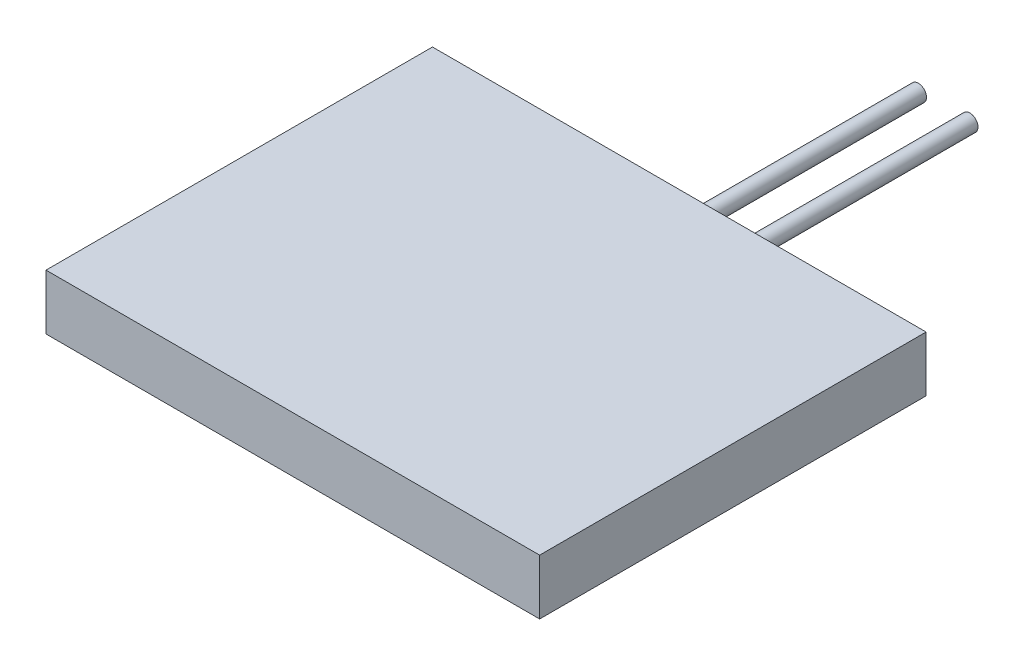
SolidWorks part; units mm, degrees
ref_plane "Front Plane" through (0, 0, 0) normal (0, 0, 1) x (1, 0, 0)
ref_plane "Top Plane" through (0, 0, 0) normal (0, 1, 0) x (1, 0, 0)
ref_plane "Right Plane" through (0, 0, 0) normal (1, 0, 0) x (0, 0, -1)
sketch "Sketch1" plane through (0, 0, 0) normal (0, 1, 0) x (1, 0, 0)
  line L1 (0, 0) -> (76.7287, 0)
  line L2 (0, 0) -> (0, -60.0682)
  line L3 (0, -60.0682) -> (76.7287, -60.0682)
  line L4 (76.7287, 0) -> (76.7287, -60.0682)
extrude "Boss-Extrude1" add sketch "Sketch1" along normal blind 8.5998
sketch "Sketch2" plane through (0, 0, 0) normal (0, 0, -1) x (-1, 0, 0)
  circle A0 centre (-48.2186, 4.9099) radius 1.27
  circle A1 centre (-40.2144, 4.9099) radius 1.27
extrude "Boss-Extrude2" add sketch "Sketch2" along normal blind 35.306
